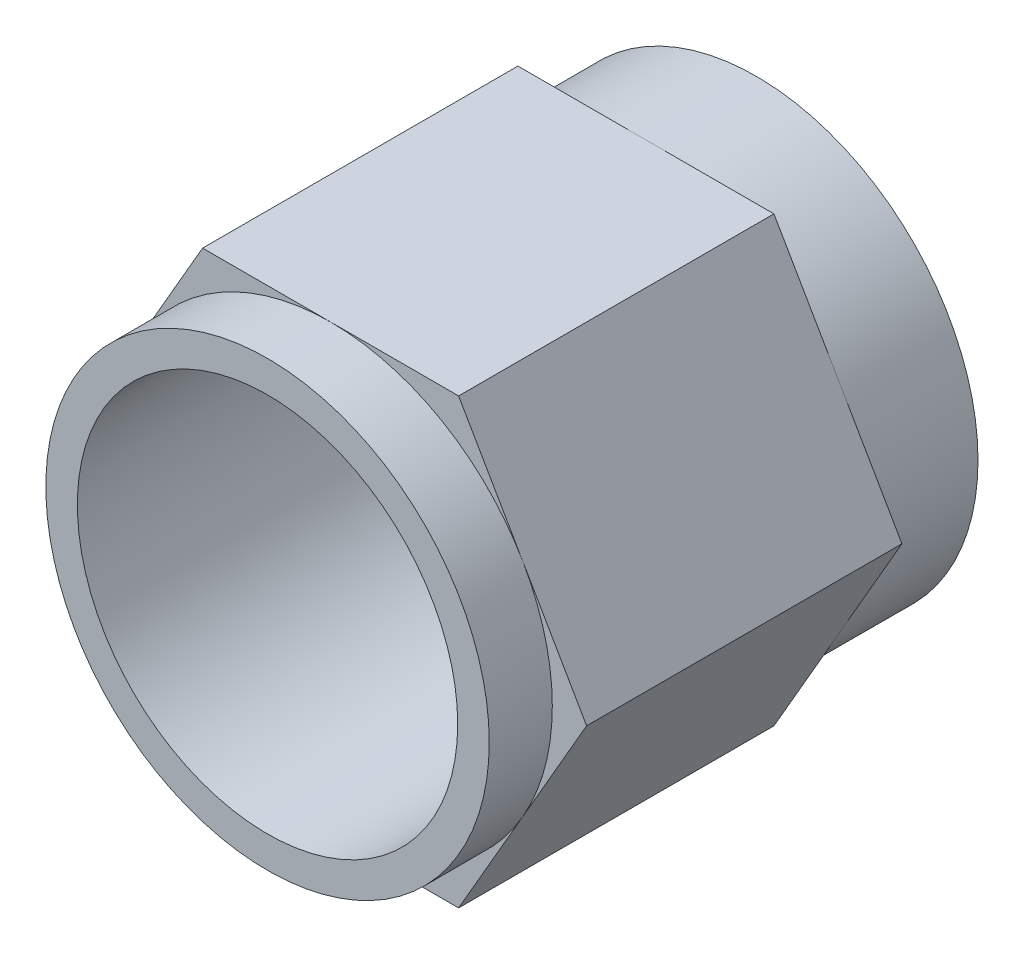
SolidWorks part; units mm, degrees
ref_plane "Front Plane" through (0, 0, 0) normal (0, 0, 1) x (1, 0, 0)
ref_plane "Top Plane" through (0, 0, 0) normal (0, 1, 0) x (1, 0, 0)
ref_plane "Right Plane" through (0, 0, 0) normal (1, 0, 0) x (0, 0, -1)
sketch "Sketch1" plane through (0, 0, 0) normal (0, 1, 0) x (1, 0, 0)
  line L0 (0, -288.7564) -> (0, 14149.0651) construction
  line L2 (0, 13.716) -> (7.1437, 13.716)
  line L3 (0, 13.716) -> (0, 12.7)
  line L4 (0, 12.7) -> (7.1437, 12.7)
  line L5 (7.1437, 13.716) -> (7.1437, 12.7)
  line L6 (7.1437, 12.7) -> (6.1277, 12.7)
  line L7 (7.1437, 12.7) -> (7.1438, -2.032)
  line L8 (7.1438, -2.032) -> (6.1278, -2.032)
  line L9 (6.1277, 12.7) -> (6.1278, -2.032)
  line L10 (0, 13.716) -> (3.9459, 13.716)
  line L11 (0, 13.716) -> (0, 14.478)
  line L12 (0, 14.478) -> (3.9459, 14.478)
  line L13 (3.9459, 13.716) -> (3.9459, 14.478)
  dimension "D1" = 15.748
  dimension "D2" = 14.2875
  dimension "D3" = 1.016
  dimension "D4" = 1.016
  dimension "D5" = 2.032
  dimension "D6" = 0.762
revolve "Revolve1" add sketch "Sketch1" angle 360 about L0
sketch "Sketch2" plane through (0, 0, 0) normal (0, 0, 1) x (1, 0, 0)
  line L1 (8.2489, 0) -> (4.1244, 7.1438)
  line L2 (4.1244, 7.1438) -> (-4.1244, 7.1438)
  line L3 (-4.1244, 7.1438) -> (-8.2489, 0)
  line L4 (-8.2489, 0) -> (-4.1244, -7.1438)
  line L5 (-4.1244, -7.1438) -> (4.1244, -7.1438)
  line L6 (4.1244, -7.1438) -> (8.2489, 0)
  circle A0 centre (0, 0) radius 7.1437 construction
  circle A1 centre (0, 0) radius 6.1278
  dimension "D1" = 14.2875
extrude "Boss-Extrude1" add sketch "Sketch2" against normal blind 10.16
